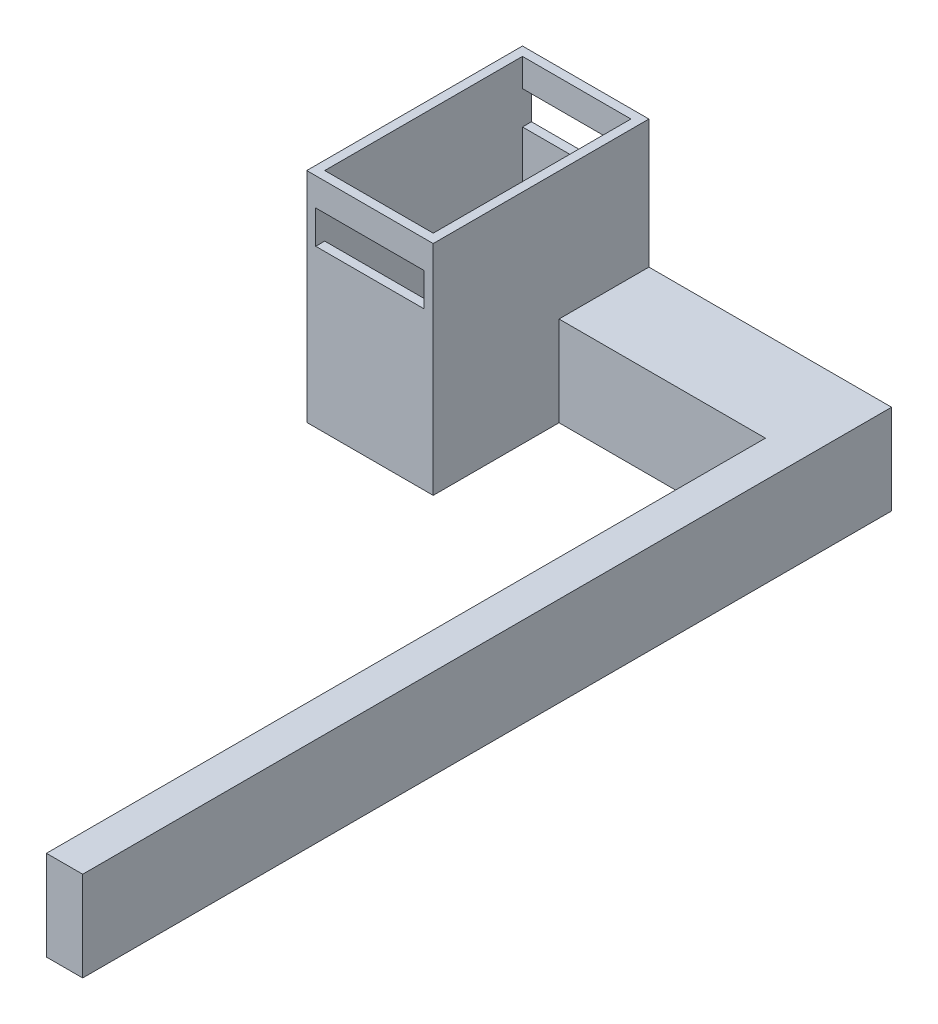
SolidWorks part; units mm, degrees
ref_plane "Front Plane" through (0, 0, 0) normal (0, 0, 1) x (1, 0, 0)
ref_plane "Top Plane" through (0, 0, 0) normal (0, 1, 0) x (1, 0, 0)
ref_plane "Right Plane" through (0, 0, 0) normal (1, 0, 0) x (0, 0, -1)
sketch "Sketch1" plane through (0, 0, 0) normal (0, 1, 0) x (1, 0, 0)
  line L1 (0, 0) -> (14.07, 0)
  line L2 (0, 0) -> (0, 24)
  line L3 (0, 24) -> (14.07, 24)
  line L4 (14.07, 0) -> (14.07, 24)
  dimension "D1" = 14.07
  dimension "D2" = 24
extrude "Boss-Extrude1" add sketch "Sketch1" along normal blind 24.27
sketch "Sketch3" plane through (0, 24.27, 0) normal (0, 1, 0) x (1, 0, 0)
  line L0 (1, 24) -> (1, 23) construction
  line L1 (14.07, 24) -> (0, 24) construction
  line L2 (1, 23) -> (0, 23) construction
  line L3 (0, 24) -> (0, 0) construction
  line L4 (0, 1) -> (1, 1) construction
  line L5 (1, 1) -> (1, 0) construction
  line L6 (0, 0) -> (14.07, 0) construction
  line L7 (13.07, 0) -> (13.07, 1) construction
  line L8 (13.07, 1) -> (14.07, 1) construction
  line L9 (14.07, 0) -> (14.07, 24) construction
  line L10 (13.07, 24) -> (13.07, 23) construction
  line L11 (13.07, 23) -> (14.07, 23) construction
  line L12 (1, 23) -> (1, 1)
  line L13 (1, 1) -> (13.07, 1)
  line L14 (13.07, 1) -> (13.07, 23)
  line L15 (13.07, 23) -> (1, 23)
  dimension "D1" = 1
  dimension "D2" = 1
  dimension "D3" = 1
  dimension "D4" = 1
  dimension "D5" = 1
  dimension "D6" = 1
  dimension "D7" = 1
  dimension "D8" = 1
extrude "Cut-Extrude1" cut sketch "Sketch3" against normal blind 23.27
sketch "Sketch5" plane through (0, 0, -24) normal (0, 0, -1) x (-1, 0, 0)
  line L0 (-14.07, 0) -> (-14.07, 17.47) construction
  line L1 (-14.07, 24.27) -> (-14.07, 0) construction
  line L2 (-14.07, 24.27) -> (-14.07, 21.1653) construction
  line L3 (-14.07, 17.47) -> (-13.07, 17.47) construction
  line L4 (-14.07, 21.1653) -> (-13.07, 21.1653) construction
  line L5 (0, 21.1653) -> (-1, 21.1653) construction
  line L6 (0, 24.27) -> (0, 0) construction
  line L7 (0, 17.47) -> (-1, 17.47) construction
  line L8 (-13.07, 21.1653) -> (-13.07, 17.47)
  line L9 (-13.07, 17.47) -> (-1, 17.47)
  line L10 (-1, 17.47) -> (-1, 21.1653)
  line L11 (-1, 21.1653) -> (-13.07, 21.1653)
  dimension "D1" = 17.47
  dimension "D2" = 3.1047
  dimension "D3" = 1
  dimension "D4" = 1
  dimension "D5" = 1
  dimension "D6" = 1
extrude "Cut-Extrude2" cut sketch "Sketch5" against normal through all both and the other way through all
sketch "Sketch6" plane through (14.07, 0, 0) normal (1, 0, 0) x (0, 0, -1)
  line L1 (24, 0) -> (14, 0)
  line L2 (24, 0) -> (24, 10)
  line L3 (24, 10) -> (14, 10)
  line L4 (14, 0) -> (14, 10)
  dimension "D1" = 10
  dimension "10" = 10
extrude "Boss-Extrude2" add sketch "Sketch6" along normal blind 27
sketch "Sketch7" plane through (0, 0, -14) normal (0, 0, 1) x (1, 0, 0)
  line L0 (41.07, 10) -> (14.07, 10) construction
  line L1 (41.07, 0) -> (37.035, 0)
  line L2 (41.07, 0) -> (41.07, 10)
  line L3 (41.07, 10) -> (37.035, 10)
  line L4 (37.035, 0) -> (37.035, 10)
  dimension "D1" = 4.035
extrude "Boss-Extrude3" add sketch "Sketch7" along normal blind 80
